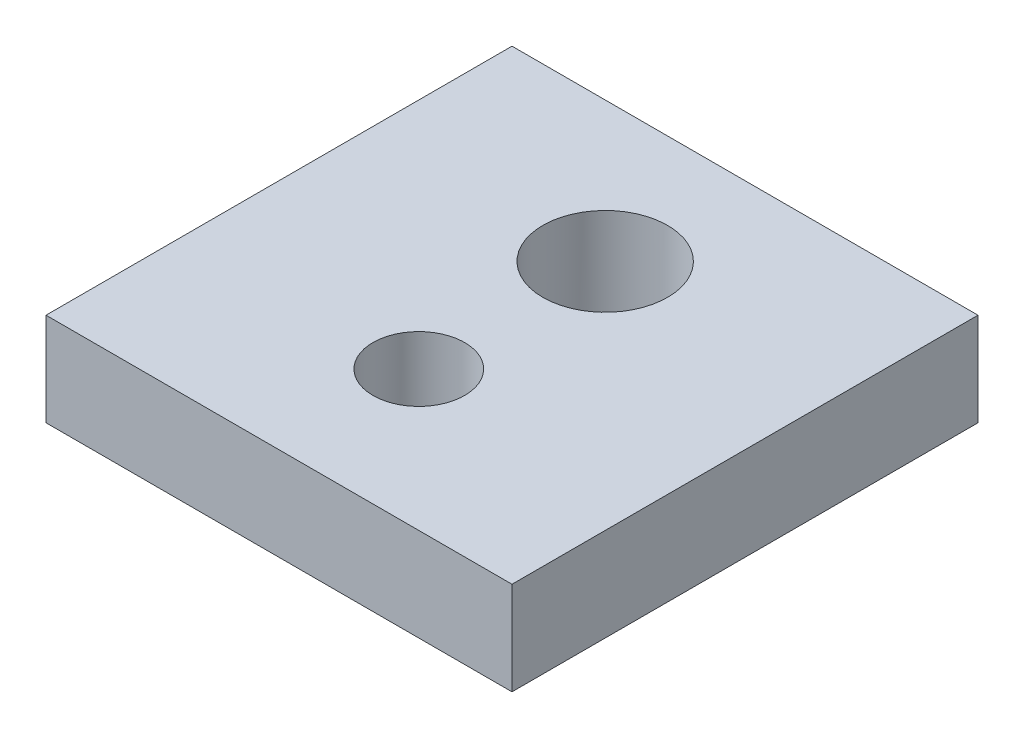
SolidWorks part; units mm, degrees
ref_plane "Front" through (0, 0, 0) normal (0, 0, 1) x (1, 0, 0)
ref_plane "Top" through (0, 0, 0) normal (0, 1, 0) x (1, 0, 0)
ref_plane "Right" through (0, 0, 0) normal (1, 0, 0) x (0, 0, -1)
sketch "Sketch1" plane through (0, 0, 0) normal (0, 1, 0) x (1, 0, 0)
  line L1 (-6.35, -6.35) -> (6.35, -6.35)
  line L2 (-6.35, -6.35) -> (-6.35, 6.35)
  line L3 (-6.35, 6.35) -> (6.35, 6.35)
  line L4 (6.35, -6.35) -> (6.35, 6.35)
  line L5 (-6.35, -6.35) -> (6.35, 6.35) construction
  line L6 (-6.35, 6.35) -> (6.35, -6.35) construction
  point P0 (0, 0)
  dimension "D1" = 12.7
  dimension "D2" = 12.7
extrude "Boss-Extrude1" add sketch "Sketch1" along normal blind 2.54
sketch "Sketch2" plane through (0, 2.54, 0) normal (0, 1, 0) x (1, 0, 0)
  line L0 (0, 6.35) -> (0, -6.35) construction
  line L1 (6.35, 6.35) -> (-6.35, 6.35) construction
  line L2 (-6.35, -6.35) -> (6.35, -6.35) construction
  point P6 (0, 2.54)
  point P7 (0, -2.54)
  dimension "D1" = 3.81
  dimension "D2" = 3.81
hole_wizard "M3 Clearance Hole1" positions "3DSketch1" profile "Sketch3" hole size "M3" standard "ANSI Metric"
sketch3d "3DSketch1"
  point P0 (0, 2.54, -2.54)
sketch "Sketch3" plane through (0, 2.54, -2.54) normal (1, 0, 0) x (0, 0, 1)
  line L0 (0, 0) -> (0, 3.5605)
  line L1 (0, 3.5605) -> (1.7, 2.539)
  line L2 (1.7, 2.539) -> (1.7, 0)
  line L5 (1.7, 0) -> (0, 0)
  line L10 (0, 3.5605) -> (-1.7, 2.539) construction
  line L11 (0, -6.35) -> (0, 107.95) construction
  dimension "Hole Dia." = 3.4
  dimension "Hole Depth" = 2.539
  dimension "Drill Angle" = 118
hole_wizard "Tap Drill for M3x0.5 Tap1" positions "3DSketch2" profile "Sketch4" hole size "M3x0.5" standard "ANSI Metric"
sketch3d "3DSketch2"
  point P0 (0, 2.54, 2.54)
sketch "Sketch4" plane through (0, 2.54, 2.54) normal (1, 0, 0) x (0, 0, 1)
  line L0 (0, 0) -> (0, 3.2901)
  line L1 (0, 3.2901) -> (1.25, 2.539)
  line L2 (1.25, 2.539) -> (1.25, 0)
  line L5 (1.25, 0) -> (0, 0)
  line L10 (0, 3.2901) -> (-1.25, 2.539) construction
  line L11 (0, -6.35) -> (0, 107.95) construction
  dimension "Hole Dia." = 2.5
  dimension "Hole Depth" = 2.539
  dimension "Drill Angle" = 118
